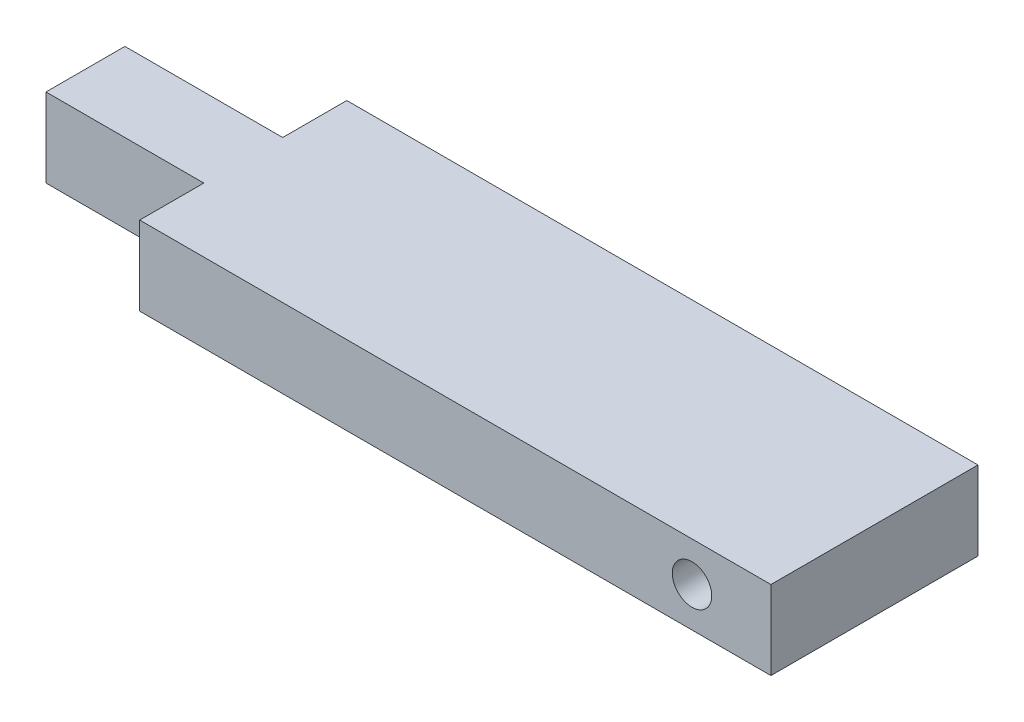
SolidWorks part; units mm, degrees
material "Ductile Iron"
ref_plane "Front Plane" through (0, 0, 0) normal (0, 0, 1) x (1, 0, 0)
ref_plane "Top Plane" through (0, 0, 0) normal (0, 1, 0) x (1, 0, 0)
ref_plane "Right Plane" through (0, 0, 0) normal (1, 0, 0) x (0, 0, -1)
sketch "Sketch1" plane through (0, 0, 0) normal (0, 1, 0) x (1, 0, 0)
  line L1 (0, 0) -> (101.6, 0)
  line L2 (0, 0) -> (0, 33.3308)
  line L3 (0, 33.3308) -> (101.6, 33.3308)
  line L4 (101.6, 0) -> (101.6, 33.3308)
  dimension "D1" = 101.6
  dimension "D2" = 33.3308
extrude "Boss-Extrude1" add sketch "Sketch1" along normal blind 12.7
sketch "Sketch2" plane through (0, 0, 0) normal (-1, 0, 0) x (0, 0, 1)
  line L0 (-16.6654, 12.7) -> (-16.6654, 0) construction
  line L1 (-33.3308, 12.7) -> (0, 12.7) construction
  line L2 (-33.3308, 0) -> (0, 0) construction
  line L4 (-23.0154, 0) -> (-10.3154, 0)
  line L5 (-23.0154, 0) -> (-23.0154, 12.7)
  line L6 (-23.0154, 12.7) -> (-10.3154, 12.7)
  line L7 (-10.3154, 0) -> (-10.3154, 12.7)
  line L8 (-23.0154, 0) -> (-10.3154, 12.7) construction
  line L9 (-23.0154, 12.7) -> (-10.3154, 0) construction
  point P6 (-16.6654, 6.35)
  dimension "D1" = 12.7
extrude "Boss-Extrude2" add sketch "Sketch2" along normal blind 25.4
sketch "Sketch4" plane through (0, 0, 0) normal (0, 0, 1) x (1, 0, 0)
  line L0 (101.6, 12.7) -> (101.6, 0) construction
  line L1 (0, 12.7) -> (101.6, 12.7) construction
  circle A0 centre (88.9, 6.35) radius 3.175
  dimension "D3" = 6.35
  dimension "D1" = 12.7
  dimension "D2" = 6.35
extrude "Cut-Extrude2" cut sketch "Sketch4" against normal through all
